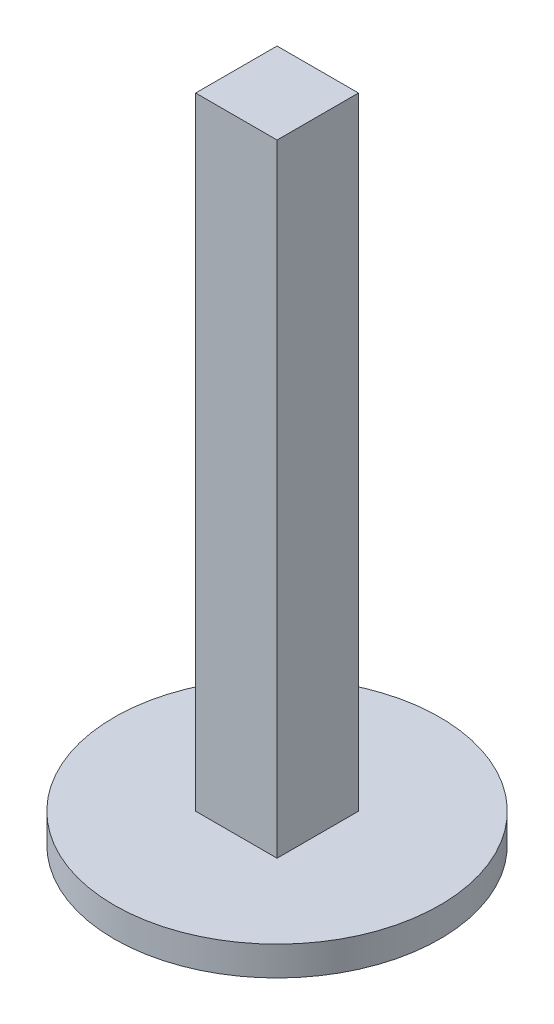
SolidWorks part; units mm, degrees
ref_plane "Front Plane" through (0, 0, 0) normal (0, 0, 1) x (1, 0, 0)
ref_plane "Top Plane" through (0, 0, 0) normal (0, 1, 0) x (1, 0, 0)
ref_plane "Right Plane" through (0, 0, 0) normal (1, 0, 0) x (0, 0, -1)
sketch "Sketch3" plane through (0, 0, 0) normal (0, 1, 0) x (1, 0, 0)
  line L0 (0, 12.7) -> (0, -12.7) construction
  line L1 (-12.7, 0) -> (12.7, 0) construction
  circle A0 centre (0, 0) radius 12.7
  circle A1 centre (0, 8.255) radius 0.762
  circle A2 centre (0, -8.3058) radius 0.762
  circle A3 centre (8.255, 0) radius 0.762
  circle A4 centre (-8.3058, 0) radius 0.762
  point P18 (0, 0)
  dimension "D1" = 25.4
  dimension "D2" = 1.524
  dimension "D3" = 1.524
  dimension "D4" = 16.5608
  dimension "D6" = 8.255
  dimension "D5" = 2
extrude "Boss-Extrude4" add sketch "Sketch3" along normal blind 2.286 contours A0
sketch "Sketch7" plane through (0, 0, 0) normal (0, 1, 0) x (1, 0, 0)
  line L6 (-3.175, 3.175) -> (3.175, 3.175)
  line L7 (-3.175, 3.175) -> (-3.175, -3.175)
  line L8 (-3.175, -3.175) -> (3.175, -3.175)
  line L9 (3.175, 3.175) -> (3.175, -3.175)
  line L10 (-3.175, 3.175) -> (3.175, -3.175) construction
  line L11 (-3.175, -3.175) -> (3.175, 3.175) construction
  point P0 (0, 0)
  dimension "D1" = 6.35
extrude "Boss-Extrude5" add sketch "Sketch7" along normal blind 50.8 contours L6 L9 L8 L7
